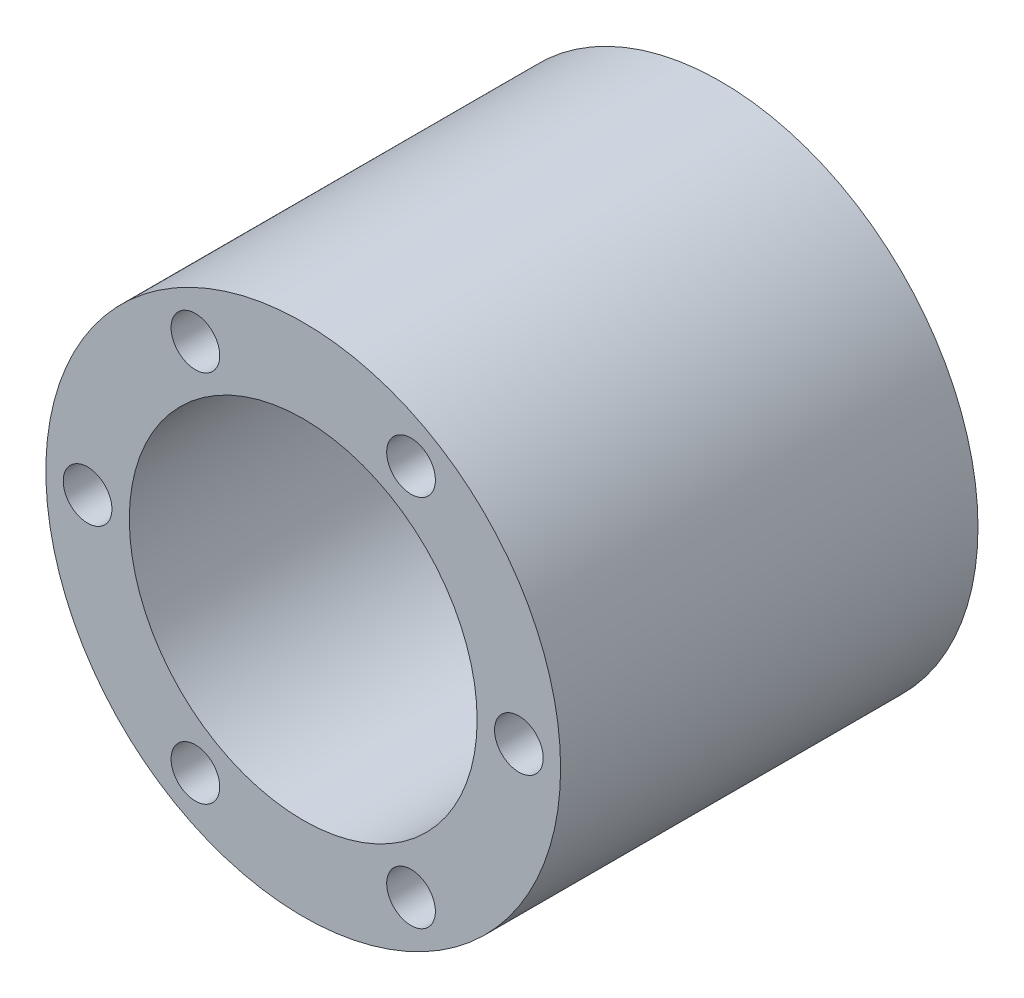
SolidWorks part; units mm, degrees
ref_plane "Front Plane" through (0, 0, 0) normal (0, 0, 1) x (1, 0, 0)
ref_plane "Top Plane" through (0, 0, 0) normal (0, 1, 0) x (1, 0, 0)
ref_plane "Right Plane" through (0, 0, 0) normal (1, 0, 0) x (0, 0, -1)
sketch "Sketch1" plane through (0, 0, 0) normal (0, 0, 1) x (1, 0, 0)
  line L0 (-15.5, 0) -> (15.5, 0) construction
  line L1 (-18.5, 0) -> (-12.5, 0) construction
  circle A0 centre (0, 0) radius 18.5
  circle A1 centre (-15.5, 0) radius 1.75
  circle A2 centre (-7.75, 13.4234) radius 1.75
  circle A3 centre (7.75, 13.4234) radius 1.75
  circle A4 centre (15.5, 0) radius 1.75
  circle A5 centre (7.75, -13.4234) radius 1.75
  circle A6 centre (-7.75, -13.4234) radius 1.75
  circle A7 centre (0, 0) radius 12.5
  point P5 (0, 0)
  dimension "D1" = 37
  dimension "D2" = 3.5
  dimension "D3" = 31
  dimension "D4" = 6
extrude "Boss-Extrude1" add sketch "Sketch1" along normal blind 30
